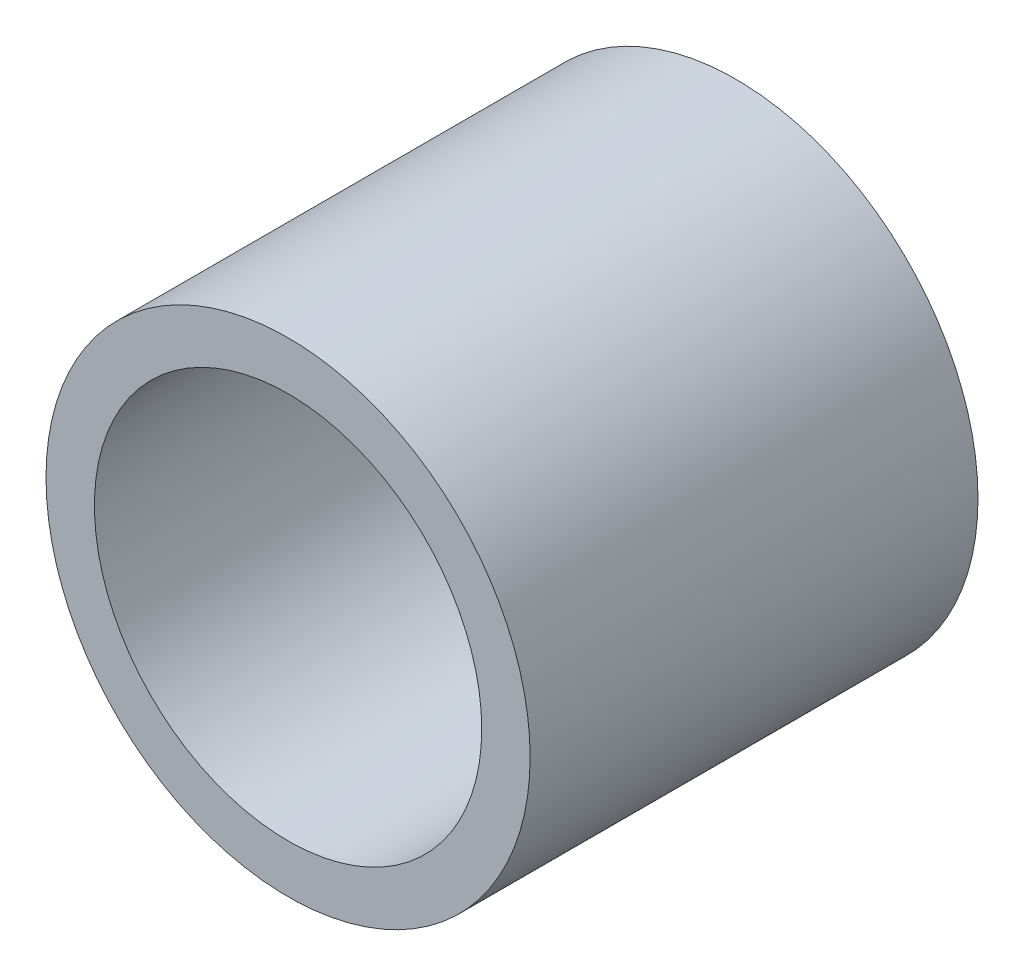
SolidWorks part; units mm, degrees
ref_plane "Front Plane" through (0, 0, 0) normal (0, 0, 1) x (1, 0, 0)
ref_plane "Top Plane" through (0, 0, 0) normal (0, 1, 0) x (1, 0, 0)
ref_plane "Right Plane" through (0, 0, 0) normal (1, 0, 0) x (0, 0, -1)
sketch "Sketch1" plane through (0, 0, 0) normal (0, 0, 1) x (1, 0, 0)
  circle A0 centre (0, 0) radius 4
  dimension "D1" = 8
extrude "Extrude-Thin1" add sketch "Sketch1" along normal blind 9.25 thin
